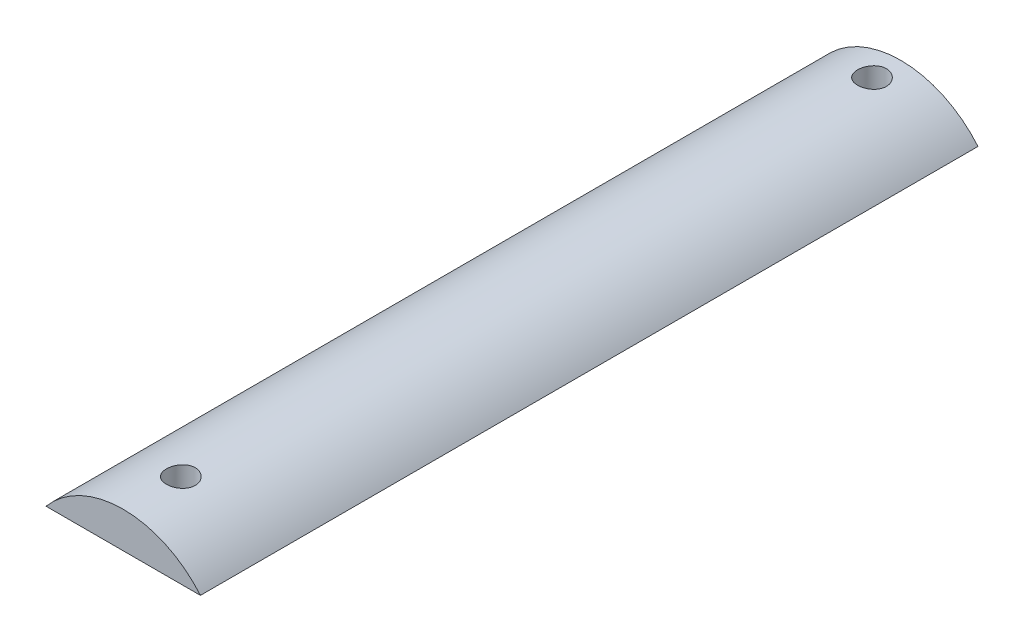
SolidWorks part; units mm, degrees
material "ABS"
ref_plane "Front Plane" through (0, 0, 0) normal (0, 0, 1) x (1, 0, 0)
ref_plane "Top Plane" through (0, 0, 0) normal (0, 1, 0) x (1, 0, 0)
ref_plane "Right Plane" through (0, 0, 0) normal (1, 0, 0) x (0, 0, -1)
sketch "Sketch1" plane through (0, 0, 0) normal (0, 0, 1) x (1, 0, 0)
  line L0 (0, 0) -> (0, 4.5) construction
  line L1 (-5.3619, 4.5) -> (5.3619, 4.5)
  circle A1 centre (0, 0) radius 7
  point P7 (0, 4.5)
  point P13 (0, 0)
extrude "Boss-Extrude1" add sketch "Sketch1" along normal blind 54 contours L1 A1
sketch "Sketch2" plane through (0, 4.5, 0) normal (0, -1, 0) x (1, 0, 0)
  line L0 (0, 0) -> (0, 2) construction
  line L1 (-5.3619, 0) -> (5.3619, 0) construction
  line L2 (0, 2) -> (0, 50) construction
  line L3 (2.3094, 50) -> (1.1547, 52)
  line L4 (2.3094, 2) -> (1.1547, 4)
  line L5 (1.1547, 4) -> (-1.1547, 4)
  line L6 (-1.1547, 4) -> (-2.3094, 2)
  line L7 (-2.3094, 2) -> (-1.1547, 0)
  line L8 (-1.1547, 0) -> (1.1547, 0)
  line L9 (1.1547, 0) -> (2.3094, 2)
  line L10 (1.1547, 52) -> (-1.1547, 52)
  line L11 (-1.1547, 52) -> (-2.3094, 50)
  line L12 (-2.3094, 50) -> (-1.1547, 48)
  line L13 (-1.1547, 48) -> (1.1547, 48)
  line L14 (1.1547, 48) -> (2.3094, 50)
  line L15 (0, 48) -> (0, 50) construction
  circle A0 centre (0, 2) radius 2 construction
  circle A1 centre (0, 50) radius 2 construction
  dimension "D1" = 2
extrude "Cut-Extrude1" cut sketch "Sketch2" against normal blind 1
sketch "Sketch3" plane through (0, 5.5, 0) normal (0, -1, 0) x (1, 0, 0)
  circle A0 centre (0, 2) radius 1
  circle A1 centre (0, 50) radius 1
  dimension "D1" = 2
extrude "Cut-Extrude2" cut sketch "Sketch3" against normal through all
